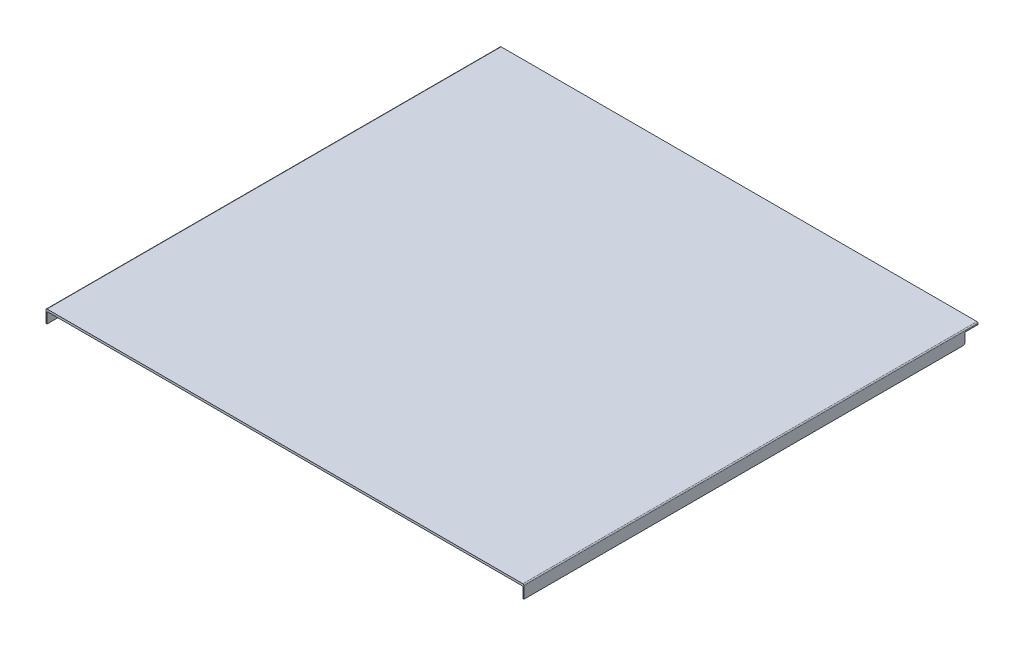
SolidWorks part; units mm, degrees
ref_plane "Front Plane" through (0, 0, 0) normal (0, 0, 1) x (1, 0, 0)
ref_plane "Top Plane" through (0, 0, 0) normal (0, 1, 0) x (1, 0, 0)
ref_plane "Right Plane" through (0, 0, 0) normal (1, 0, 0) x (0, 0, -1)
sketch "Sketch1" plane through (0, 0, 0) normal (0, 1, 0) x (1, 0, 0)
  line L1 (-221, -210) -> (221, -210)
  line L2 (-221, -210) -> (-221, 210)
  line L3 (-221, 210) -> (221, 210)
  line L4 (221, -210) -> (221, 210)
  line L5 (-221, -210) -> (221, 210) construction
  line L6 (-221, 210) -> (221, -210) construction
  point P0 (0, 0)
  dimension "D1" = 442
  dimension "D2" = 420
extrude "Boss-Extrude1" add sketch "Sketch1" along normal blind 2
sketch "Sketch2" plane through (0, 0, 0) normal (0, -1, 0) x (1, 0, 0)
  line L0 (0, 0) -> (0, 210) construction
  line L1 (-221, 210) -> (221, 210) construction
  line L2 (220, 210) -> (220, -198)
  line L3 (-221, 210) -> (-220, 210)
  line L4 (-221, 210) -> (-221, -198)
  line L5 (-221, -198) -> (-220, -198)
  line L6 (-220, 210) -> (-220, -198)
  line L7 (221, -198) -> (220, -198)
  line L8 (221, 210) -> (221, -198)
  line L9 (221, 210) -> (220, 210)
  line L10 (221, -210) -> (-221, -210) construction
  dimension "D1" = 1
  dimension "D2" = 12
extrude "Boss-Extrude2" add sketch "Sketch2" along normal blind 10
fillet "Fillet1" radius 2 2 edges at (220.5, -10, -198) (-220.5, -10, -198)
fillet "Fillet2" radius 0.5 2 edges at (220.5, 0, -198) (-220.5, 0, -198)
fillet "Fillet3" radius 1 2 edges at (221, 2, 0) (-221, 2, 0)
fillet "Fillet4" radius 0.5 2 edges at (-220, 0, 5.75) (220, 0, 5.75)
